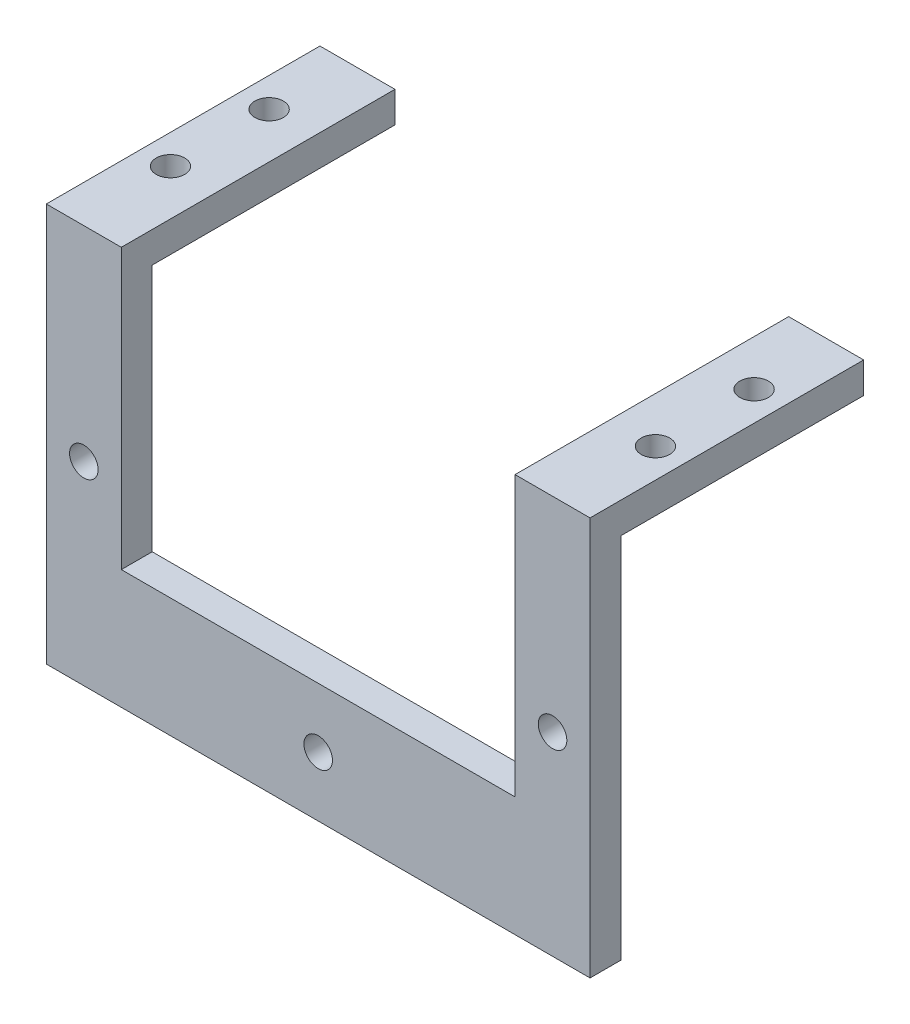
SolidWorks part; units mm, degrees
ref_plane "Front Plane" through (0, 0, 0) normal (0, 0, 1) x (1, 0, 0)
ref_plane "Top Plane" through (0, 0, 0) normal (0, 1, 0) x (1, 0, 0)
ref_plane "Right Plane" through (0, 0, 0) normal (1, 0, 0) x (0, 0, -1)
sketch "Sketch2" plane through (0, 0, 0) normal (0, 0, 1) x (1, 0, 0)
  line L0 (0, 0) -> (0, 39.7945) construction
  line L1 (-28, -6.1445) -> (28, -6.1445)
  line L2 (-28, -6.1445) -> (-28, 2.3729)
  line L3 (-20.275, 6.1445) -> (20.275, 6.1445)
  line L4 (28, -6.1445) -> (28, 12.5763)
  line L5 (0, 0) -> (-14.4392, 0) construction
  line L8 (-28, 2.3729) -> (-28, 34.8945)
  line L9 (-28, 34.8945) -> (-20.275, 34.8945)
  line L10 (-20.275, 6.1445) -> (-20.275, 34.8945)
  line L12 (28, 12.5763) -> (28, 34.8945)
  line L13 (28, 34.8945) -> (20.275, 34.8945)
  line L14 (20.275, 6.1445) -> (20.275, 34.8945)
  point P0 (0, 0)
  dimension "D1" = 56
  dimension "D2" = 28.75
  dimension "D3" = 12.2889
  dimension "D4" = 40.55
extrude "Boss-Extrude4" add sketch "Sketch2" along normal mid plane 3.18
sketch "Sketch5" plane through (0, 34.8945, 0) normal (0, 1, 0) x (1, 0, 0)
  line L0 (28, -1.59) -> (20.275, -1.59) construction
  line L1 (28, 1.59) -> (20.275, 1.59)
  line L2 (28, 1.59) -> (28, 26.59)
  line L3 (28, 26.59) -> (20.275, 26.59)
  line L4 (20.275, 1.59) -> (20.275, 26.59)
  line L5 (24.975, 8.17) -> (24.975, 25.7506) construction
  circle A0 centre (24.975, 8.17) radius 1.47
  circle A1 centre (24.975, 18.33) radius 1.47
  dimension "D3" = 2.94
  dimension "D4" = 4.7
  dimension "D5" = 10.16
  dimension "D1" = 9.76
  dimension "D2" = 25
extrude "Boss-Extrude5" add sketch "Sketch5" against normal blind 3.18
mirror "Mirror1" about plane through (0, 0, 0) normal (1, 0, 0) of "Boss-Extrude5"
sketch "Sketch7" plane through (0, 0, -1.59) normal (0, 0, -1) x (-1, 0, 0)
  line L0 (-20.275, 13.8555) -> (-28, 13.8555) construction
  line L1 (-20.275, 34.8945) -> (-20.275, 6.1445) construction
  line L2 (28, 13.8555) -> (20.275, 13.8555) construction
  line L3 (28, 31.7145) -> (28, -6.1445) construction
  line L4 (20.275, 6.1445) -> (20.275, 31.7145) construction
  line L5 (28, -6.1445) -> (-28, -6.1445) construction
  line L6 (-28, -6.1445) -> (-28, 34.8945) construction
  circle A0 centre (0, 0) radius 1.47
  circle A1 centre (24.1375, 13.8555) radius 1.47
  circle A2 centre (-24.1375, 13.8555) radius 1.47
  point P22 (-24.1375, 13.8555)
  dimension "D1" = 2.94
  dimension "D2" = 20
extrude "Cut-Extrude1" cut sketch "Sketch7" against normal through all
